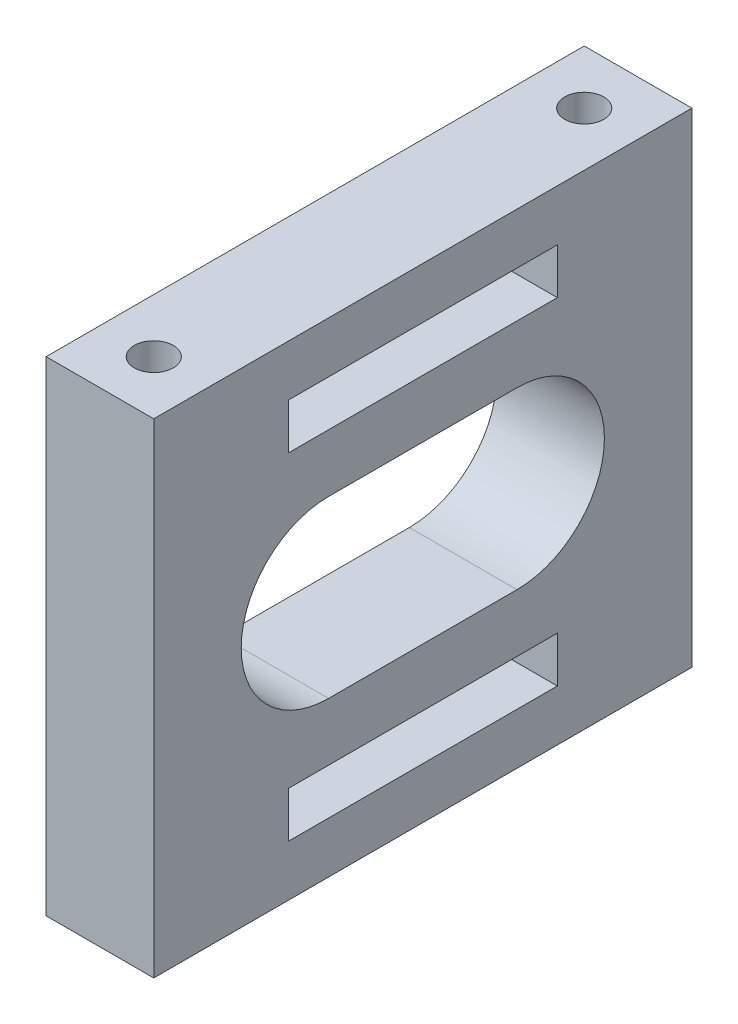
SolidWorks part; units mm, degrees
ref_plane "Front" through (0, 0, 0) normal (0, 0, 1) x (1, 0, 0)
ref_plane "Top" through (0, 0, 0) normal (0, 1, 0) x (1, 0, 0)
ref_plane "Right" through (0, 0, 0) normal (1, 0, 0) x (0, 0, -1)
sketch "Sketch1" plane through (0, 0, 0) normal (1, 0, 0) x (0, 0, -1)
  line L1 (0, 0) -> (40, 0)
  line L2 (0, 0) -> (0, -36)
  line L3 (0, -36) -> (40, -36)
  line L4 (40, 0) -> (40, -36)
  dimension "D1" = 40
  dimension "D2" = 36
extrude "Boss-Extrude1" add sketch "Sketch1" along normal blind 8
sketch "Sketch2" plane through (8, 0, 0) normal (1, 0, 0) x (0, 0, -1)
  line L0 (40, 0) -> (0, 0) construction
  line L1 (0, 0) -> (0, -36) construction
  circle A0 centre (20, -18) radius 6
  dimension "D1" = 12
  dimension "D2" = 18
  dimension "D3" = 20
extrude "Cut-Extrude1" cut sketch "Sketch2" against normal through all
sketch "Sketch3" plane through (8, 0, 0) normal (1, 0, 0) x (0, 0, -1)
  line L0 (40, -36) -> (40, 0) construction
  line L1 (10, -3.8) -> (30, -3.8)
  line L2 (10, -3.8) -> (10, -7.2)
  line L3 (10, -7.2) -> (30, -7.2)
  line L4 (30, -3.8) -> (30, -7.2)
  line L5 (40, 0) -> (0, 0) construction
  line L6 (10, -32.2) -> (30, -32.2)
  line L7 (10, -28.8) -> (30, -28.8)
  line L8 (30, -28.8) -> (30, -32.2)
  line L9 (10, -28.8) -> (10, -32.2)
  dimension "D1" = 3.4
  dimension "D2" = 20
  dimension "D3" = 10
  dimension "D4" = 3.8
  dimension "D5" = 2
extrude "Cut-Extrude2" cut sketch "Sketch3" against normal through all
sketch "Sketch6" plane through (0, 0, 0) normal (0, 1, 0) x (1, 0, 0)
  line L0 (8, 40) -> (8, 0) construction
  line L1 (8, 0) -> (0, 0) construction
  circle A0 centre (4, 4) radius 1.45
  circle A1 centre (4, 36) radius 1.45
  dimension "D1" = 2.9
  dimension "D4" = 2
  dimension "D2" = 4
  dimension "D3" = 4
extrude "Cut-Extrude3" cut sketch "Sketch6" against normal through all
sketch "Sketch7" plane through (8, 0, 0) normal (1, 0, 0) x (0, 0, -1)
  line L0 (0, -36) -> (40, -36) construction
  line L1 (13, -24.5) -> (27, -24.5)
  line L2 (0, 0) -> (0, -36) construction
  line L3 (40, -36) -> (40, 0) construction
  line L4 (13, -11.5) -> (27, -11.5)
  line L5 (27, -24.5) -> (27, -11.5)
  line L6 (13, -24.5) -> (13, -11.5)
  circle A0 centre (27, -18) radius 6.5
  circle A1 centre (13, -18) radius 6.5
  dimension "D5" = 13
  dimension "D6" = 13
  dimension "D1" = 18
  dimension "D2" = 18
  dimension "D3" = 13
  dimension "D4" = 13
extrude "Cut-Extrude4" cut sketch "Sketch7" against normal through all contours A1 | L1 L5 L4 L6 | A0
equation "\"offset\"= 0.4"
equation "\"D1@Sketch3\"=\"offset\"+3"
